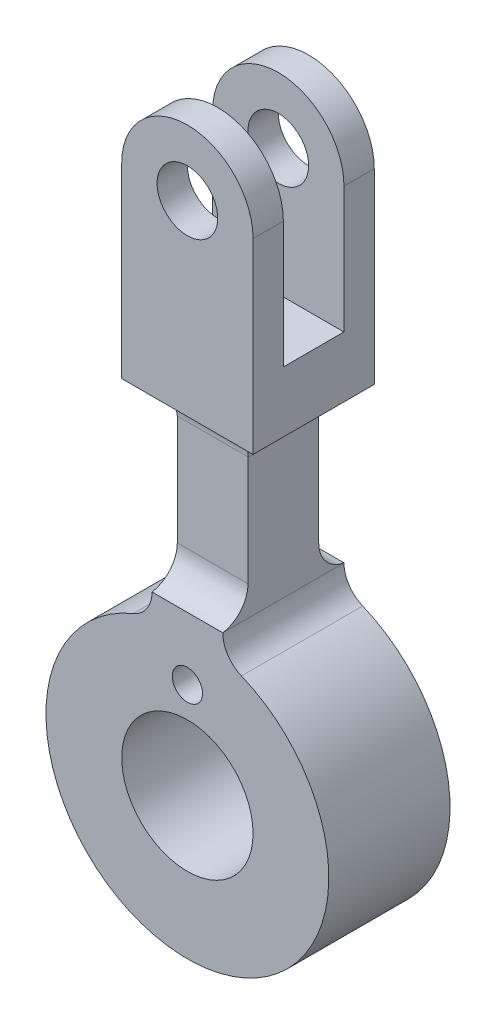
SolidWorks part; units mm, degrees
material "Plain Carbon Steel"
ref_plane "Front Plane" through (0, 0, 0) normal (0, 0, 1) x (1, 0, 0)
ref_plane "Top Plane" through (0, 0, 0) normal (0, 1, 0) x (1, 0, 0)
ref_plane "Right Plane" through (0, 0, 0) normal (1, 0, 0) x (0, 0, -1)
sketch "Sketch1" plane through (0, 0, 0) normal (0, 0, 1) x (1, 0, 0)
  line L0 (0, 0) -> (0, -50000) construction
  line L1 (-3.5, 15.7083) -> (-3.5, 29.5)
  line L2 (-6.5, 32.5) -> (-6.5, 51)
  line L3 (3.5, 15.7083) -> (3.5, 29.5)
  line L4 (6.5, 32.5) -> (6.5, 51)
  circle A0 centre (0, 0) radius 6.5
  arc A1 (-5.3529, 12.9362) -> (5.3529, 12.9362) centre (0, 0) ccw
  arc A2 (-3.5, 15.7083) -> (-5.3529, 12.9362) centre (-6.5, 15.7083) cw
  arc A3 (-3.5, 29.5) -> (-6.5, 32.5) centre (-6.5, 29.5) ccw
  circle A4 centre (0, 9.5) radius 1.5
  arc A5 (3.5, 15.7083) -> (5.3529, 12.9362) centre (6.5, 15.7083) ccw
  arc A6 (3.5, 29.5) -> (6.5, 32.5) centre (6.5, 29.5) cw
  arc A7 (-6.5, 51) -> (6.5, 51) centre (0, 51) cw
  circle A8 centre (0, 51) radius 3
  point P4 (0, 57.5)
  point P16 (0, 0)
  point P17 (6.5, 30.4462)
  dimension "D1" = 28
  dimension "D2" = 13
  dimension "D3" = 3
  dimension "D4" = 3
  dimension "D7" = 3
  dimension "D9" = 6
  dimension "D5" = 7
  dimension "D6" = 51
  dimension "D8" = 9.5
  dimension "D10" = 25
extrude "Boss-Extrude1" add sketch "Sketch1" along normal mid plane 12
sketch "Sketch2" plane through (0, 0, 0) normal (1, 0, 0) x (0, 0, -1)
  line L0 (0, 0) -> (0, 50000) construction
  line L1 (-6, 32.5) -> (-6, 15.7083)
  line L2 (-3.5, 29.542) -> (-3.5, 18.6663)
  line L3 (6, 32.5) -> (6, 15.7083)
  line L4 (3.5, 29.542) -> (3.5, 18.6663)
  line L5 (6, 57.5) -> (-6, 57.5) construction
  line L6 (-3, 38.5) -> (3, 38.5)
  line L7 (-3, 38.5) -> (-3, 57.5)
  line L8 (-3, 57.5) -> (3, 57.5)
  line L9 (3, 38.5) -> (3, 57.5)
  line L10 (-3, 38.5) -> (3, 57.5) construction
  line L11 (-3, 57.5) -> (3, 38.5) construction
  arc A0 (-6, 32.5) -> (-3.5, 29.542) centre (-6.5, 29.542) cw
  arc A1 (-6, 15.7083) -> (-3.5, 18.6663) centre (-6.5, 18.6663) ccw
  arc A2 (6, 15.7083) -> (3.5, 18.6663) centre (6.5, 18.6663) cw
  arc A3 (6, 32.5) -> (3.5, 29.542) centre (6.5, 29.542) ccw
  point P30 (0, 48)
  dimension "D1" = 3
  dimension "3" = 3
  dimension "D2" = 7
  dimension "D3" = 6
  dimension "D4" = 19
extrude "Cut-Extrude1" cut sketch "Sketch2" against normal through all both and the other way through all
